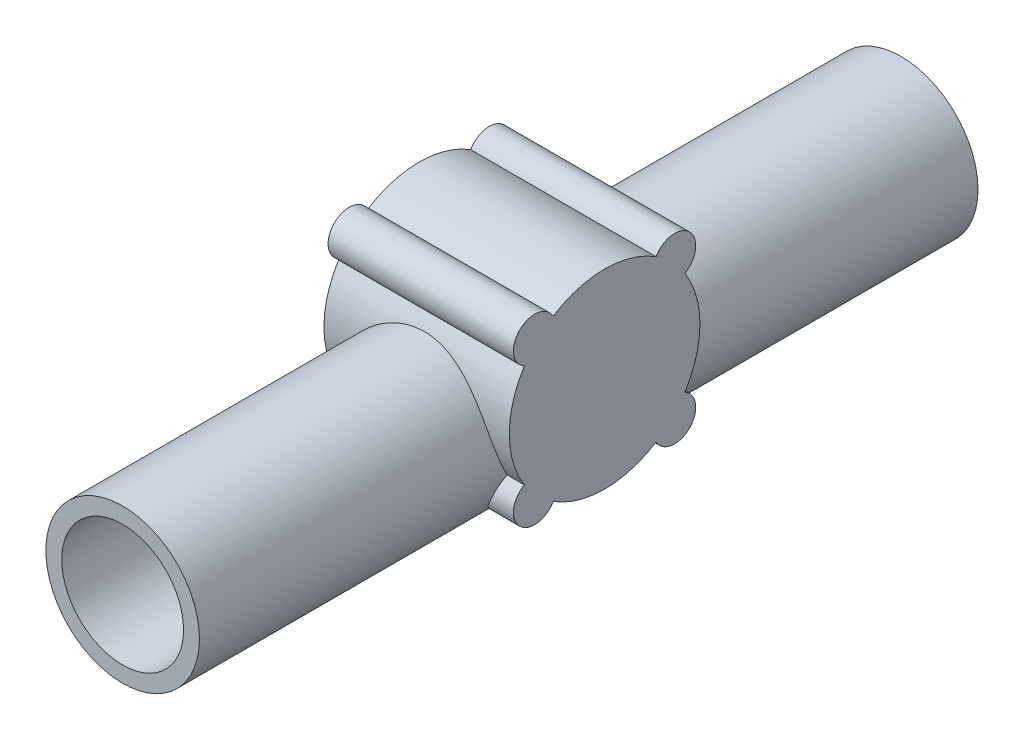
SolidWorks part; units mm, degrees
ref_plane "Front Plane" through (0, 0, 0) normal (0, 0, 1) x (1, 0, 0)
ref_plane "Top Plane" through (0, 0, 0) normal (0, 1, 0) x (1, 0, 0)
ref_plane "Right Plane" through (0, 0, 0) normal (1, 0, 0) x (0, 0, -1)
sketch "Sketch1" plane through (0, 0, 0) normal (0, 0, 1) x (1, 0, 0)
  circle A0 centre (0, 0) radius 14.5
extrude "Boss-Extrude1" add sketch "Sketch1" along normal blind 147
sketch "Sketch3" plane through (0, 0, 0) normal (1, 0, 0) x (0, 0, -1)
  circle A0 centre (-73.5, 7.25) radius 18
extrude "Boss-Extrude2" add sketch "Sketch3" along normal blind 17.5
sketch "Sketch4" plane through (0, 0, 0) normal (-1, 0, 0) x (0, 0, 1)
  circle A0 centre (73.5, 7.25) radius 18
extrude "Boss-Extrude3" add sketch "Sketch4" along normal blind 17.5
sketch "Sketch5" plane through (17.5, 0, 0) normal (1, 0, 0) x (0, 0, -1)
  circle A1 centre (-60.2883, 20.4617) radius 4
  circle A2 centre (-86.7117, 20.4617) radius 4
  circle A3 centre (-60.2883, -5.9617) radius 4
  circle A4 centre (-86.7117, -5.9617) radius 4
extrude "Boss-Extrude4" add sketch "Sketch5" against normal blind 35
sketch "Sketch2" plane through (0, 0, 147) normal (0, 0, 1) x (1, 0, 0)
  circle A0 centre (0, 0) radius 11.5
extrude "Cut-Extrude1" cut sketch "Sketch2" against normal blind 147
